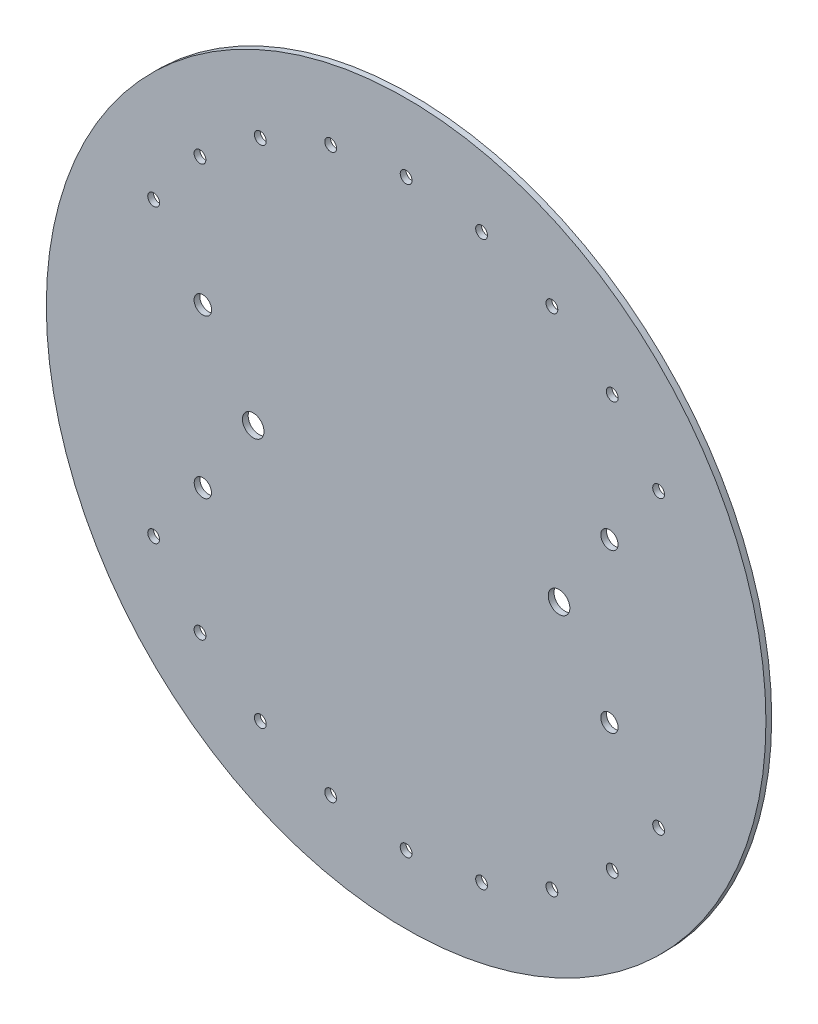
SolidWorks part; units mm, degrees
material "1345 Alloy"
ref_plane "Front Plane" through (0, 0, 0) normal (0, 0, 1) x (1, 0, 0)
ref_plane "Top Plane" through (0, 0, 0) normal (0, 1, 0) x (1, 0, 0)
ref_plane "Right Plane" through (0, 0, 0) normal (1, 0, 0) x (0, 0, -1)
sketch "Sketch1" plane through (0, 0, 0) normal (0, 0, 1) x (1, 0, 0)
  circle A0 centre (0, 0) radius 250
  dimension "D1" = 500
extrude "Boss-Extrude1" add sketch "Sketch1" along normal blind 4
sketch "Sketch5" plane through (0, 0, 4) normal (0, 0, 1) x (1, 0, 0)
  line L8 (-113.9904, 167.4371) -> (-101.9904, 146.6525) construction
  line L10 (88.0096, 182.4371) -> (76.0096, 161.6525) construction
  line L11 (-101.9904, 146.6525) -> (-76.0096, 161.6525) construction
  line L14 (-76.0096, 161.6525) -> (-88.0096, 182.4371) construction
  line L18 (-88.0096, 182.4371) -> (-113.9904, 167.4371) construction
  line L19 (-88.0096, 182.4371) -> (-101.9904, 146.6525) construction
  line L20 (-113.9904, 167.4371) -> (-76.0096, 161.6525) construction
  line L21 (0, 0) -> (-95, 164.5448) construction
  line L22 (76.0096, 161.6525) -> (101.9904, 146.6525) construction
  line L23 (101.9904, 146.6525) -> (113.9904, 167.4371) construction
  line L24 (113.9904, 167.4371) -> (88.0096, 182.4371) construction
  line L29 (113.9904, 167.4371) -> (76.0096, 161.6525) construction
  line L34 (88.0096, 182.4371) -> (101.9904, 146.6525) construction
  line L39 (0, 0) -> (95, 164.5448) construction
  line L59 (113.9904, -167.4371) -> (101.9904, -146.6525) construction
  line L64 (101.9904, -146.6525) -> (76.0096, -161.6525) construction
  line L69 (76.0096, -161.6525) -> (88.0096, -182.4371) construction
  line L74 (88.0096, -182.4371) -> (113.9904, -167.4371) construction
  line L84 (88.0096, -182.4371) -> (101.9904, -146.6525) construction
  line L85 (113.9904, -167.4371) -> (76.0096, -161.6525) construction
  line L86 (0, 0) -> (95, -164.5448) construction
  line L87 (-88.0096, -182.4371) -> (-76.0096, -161.6525) construction
  line L88 (-76.0096, -161.6525) -> (-101.9904, -146.6525) construction
  line L89 (-101.9904, -146.6525) -> (-113.9904, -167.4371) construction
  line L90 (-113.9904, -167.4371) -> (-88.0096, -182.4371) construction
  line L91 (-113.9904, -167.4371) -> (-76.0096, -161.6525) construction
  line L92 (-88.0096, -182.4371) -> (-101.9904, -146.6525) construction
  line L93 (0, 0) -> (-95, -164.5448) construction
  line L101 (-202, -15) -> (-178, -15) construction
  line L102 (-178, -15) -> (-178, 15) construction
  line L103 (-178, 15) -> (-202, 15) construction
  line L104 (-202, 15) -> (-202, -15) construction
  line L105 (-202, 15) -> (-178, -15) construction
  line L106 (-202, -15) -> (-178, 15) construction
  line L107 (0, 0) -> (-190, 0) construction
  line L108 (202, 15) -> (178, 15) construction
  line L109 (178, 15) -> (178, -15) construction
  line L110 (178, -15) -> (202, -15) construction
  line L111 (202, -15) -> (202, 15) construction
  line L112 (202, -15) -> (178, 15) construction
  line L113 (202, 15) -> (178, -15) construction
  line L114 (0, 0) -> (190, 0) construction
  circle A62 centre (-101.9904, 146.6525) radius 2
  circle A63 centre (-76.0096, 161.6525) radius 2
  circle A64 centre (-113.9904, 167.4371) radius 2
  circle A65 centre (-88.0096, 182.4371) radius 2
  circle A70 centre (76.0096, 161.6525) radius 2
  circle A71 centre (101.9904, 146.6525) radius 2
  circle A72 centre (88.0096, 182.4371) radius 2
  circle A73 centre (113.9904, 167.4371) radius 2
  circle A82 centre (101.9904, -146.6525) radius 2
  circle A83 centre (76.0096, -161.6525) radius 2
  circle A84 centre (113.9904, -167.4371) radius 2
  circle A85 centre (88.0096, -182.4371) radius 2
  circle A86 centre (-76.0096, -161.6525) radius 2
  circle A87 centre (-101.9904, -146.6525) radius 2
  circle A88 centre (-88.0096, -182.4371) radius 2
  circle A89 centre (-113.9904, -167.4371) radius 2
  circle A94 centre (-178, -15) radius 2 [skipped]
  circle A95 centre (-178, 15) radius 2 [skipped]
  circle A96 centre (-202, -15) radius 2 [skipped]
  circle A97 centre (-202, 15) radius 2 [skipped]
  circle A98 centre (178, 15) radius 2 [skipped]
  circle A99 centre (178, -15) radius 2 [skipped]
  circle A100 centre (202, 15) radius 2 [skipped]
  circle A101 centre (202, -15) radius 2 [skipped]
  point P5 (0, 0)
  point P6 (0, 0)
  point P15 (0, 0)
  point P17 (0, 0)
  point P18 (0, 0)
  point P27 (0, 0)
  point P29 (0, 0)
  point P30 (0, 0)
  point P33 (-141.1925, 81.5175)
  point P35 (0, 0)
  point P41 (0, 0)
  point P43 (0, 0)
  point P44 (0, 0)
  point P49 (0, 0)
  point P54 (0, 0)
  point P56 (0, 0)
  point P57 (0, 0)
  point P66 (0, 0)
  point P67 (0, 0)
  point P193 (0, 0)
  dimension "D1" = 6
extrude "Cut-Extrude3" [suppressed] cut sketch "Sketch5" against normal blind 10
sketch "Sketch12" plane through (0, 0, 4) normal (0, 0, 1) x (1, 0, 0)
  line L0 (-141.2381, 0) -> (-106.2381, 0) construction
  line L9 (-141.2381, 55) -> (-141.2381, -55) construction
  circle A0 centre (-141.2381, 55) radius 6.1
  circle A4 centre (-106.2381, 0) radius 7.5
  circle A5 centre (106.2381, 0) radius 7.5
  circle A12 centre (-141.2381, -55) radius 6
  circle A13 centre (141.2381, -55) radius 6
  circle A14 centre (141.2381, 55) radius 6
  circle A16 centre (0, -202.5562) radius 4.1
  circle A17 centre (-52.4254, -195.6542) radius 4.1
  circle A18 centre (-101.2781, -175.4188) radius 4.1
  circle A19 centre (-143.2288, -143.2288) radius 4.1
  circle A20 centre (-175.4188, -101.2781) radius 4.1
  circle A24 centre (-175.4188, 101.2781) radius 4.1
  circle A25 centre (-143.2288, 143.2288) radius 4.1
  circle A26 centre (-101.2781, 175.4188) radius 4.1
  circle A27 centre (-52.4254, 195.6542) radius 4.1
  circle A28 centre (0, 202.5562) radius 4.1
  circle A29 centre (52.4254, 195.6542) radius 4.1
  circle A30 centre (101.2781, 175.4188) radius 4.1
  circle A31 centre (143.2288, 143.2288) radius 4.1
  circle A32 centre (175.4188, 101.2781) radius 4.1
  circle A36 centre (175.4188, -101.2781) radius 4.1
  circle A37 centre (143.2288, -143.2288) radius 4.1
  circle A38 centre (101.2781, -175.4188) radius 4.1
  circle A39 centre (52.4254, -195.6542) radius 4.1
  point P1 (0, 0)
  point P9 (0, 0)
  point P23 (0, 0)
  point P42 (0, 0)
  point P89 (0, 0)
  dimension "D8" = 12.2
  dimension "D3" = 15
  dimension "D11" = 8.2
  dimension "D14" = 15
  dimension "D10" = 12
  dimension "D1" = 35
  dimension "D4" = 2
extrude "Cut-Extrude7" cut sketch "Sketch12" against normal through all and the other way through all
